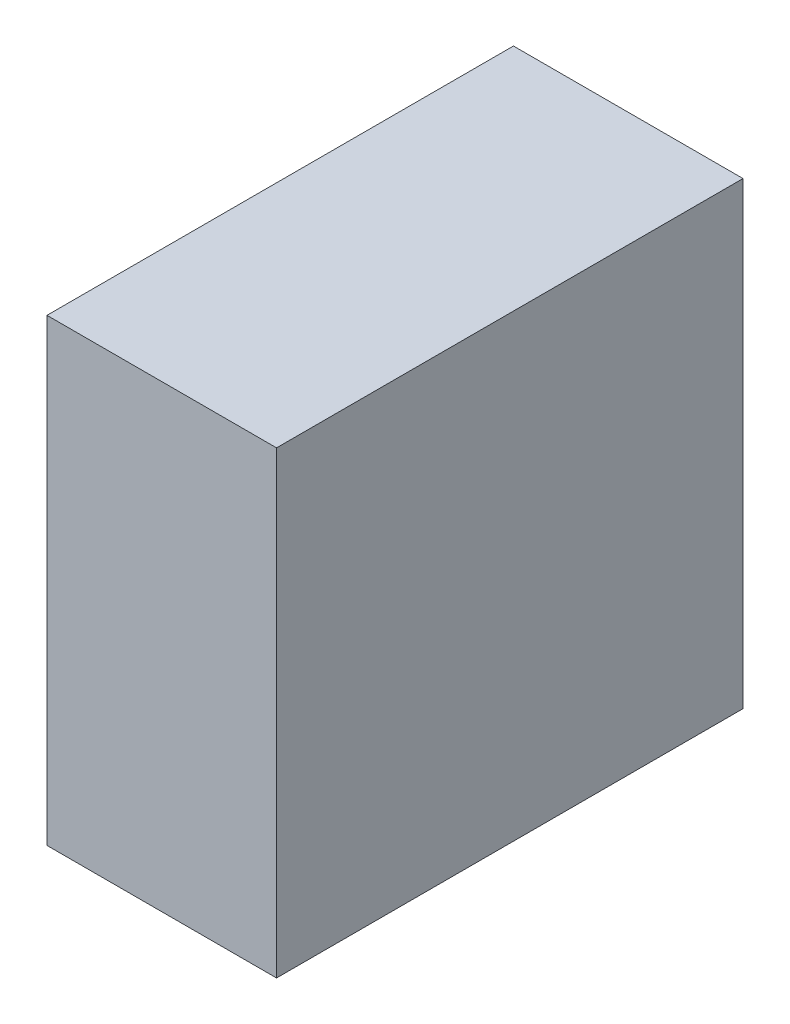
SolidWorks part; units mm, degrees
material "5052-H32"
ref_plane "Front Plane" through (0, 0, 0) normal (0, 0, 1) x (1, 0, 0)
ref_plane "Top Plane" through (0, 0, 0) normal (0, 1, 0) x (1, 0, 0)
ref_plane "Right Plane" through (0, 0, 0) normal (1, 0, 0) x (0, 0, -1)
sketch "Sketch3" plane through (0, 0, 0) normal (0, 0, 1) x (1, 0, 0)
  line L1 (-100, 100) -> (0, 100)
  line L2 (-100, 100) -> (-100, -100)
  line L3 (-100, -100) -> (0, -100)
  line L4 (0, 100) -> (0, -100)
  point P4 (0, 0)
  dimension "D1" = 200
  dimension "D2" = 100
extrude "Boss-Extrude1" add sketch "Sketch3" along normal blind 203.2 contours L1 L4 L3 L2
